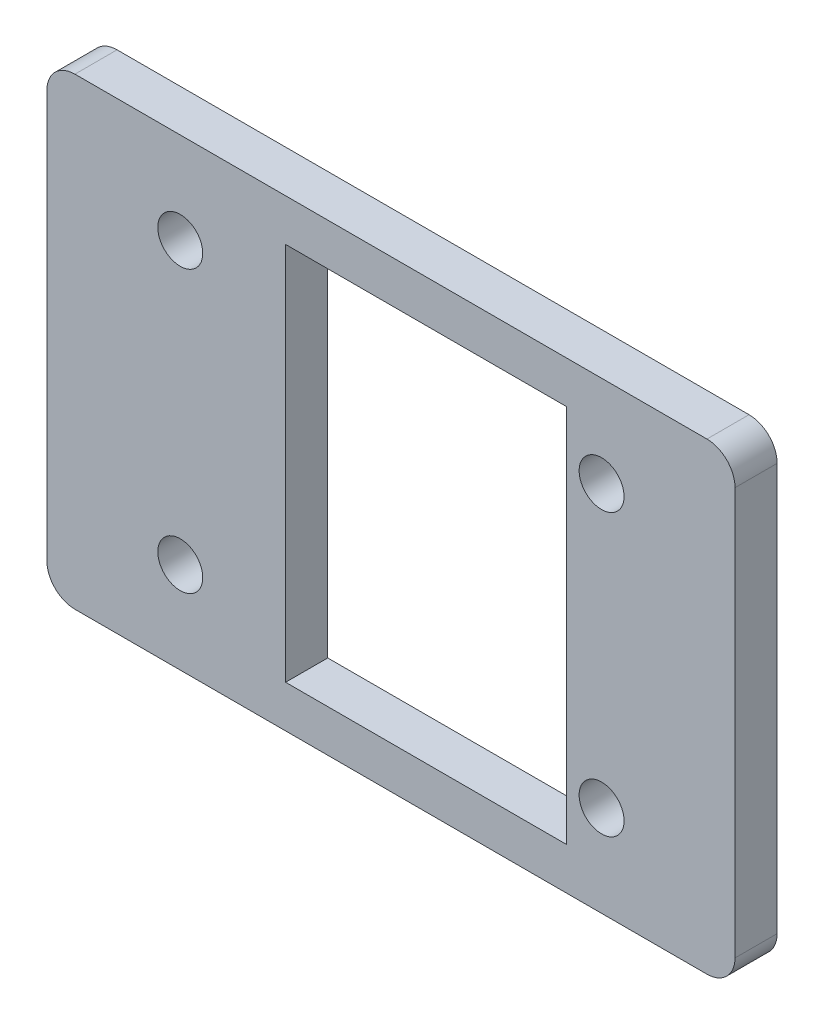
SolidWorks part; units mm, degrees
ref_plane "Front" through (0, 0, 0) normal (0, 0, 1) x (1, 0, 0)
ref_plane "Top" through (0, 0, 0) normal (0, 1, 0) x (1, 0, 0)
ref_plane "Right" through (0, 0, 0) normal (1, 0, 0) x (0, 0, -1)
sketch "Sketch1" plane through (0, 0, 0) normal (0, 0, 1) x (1, 0, 0)
  line L1 (-19.1679, 16.2582) -> (29.8321, 16.2582)
  line L2 (-19.1679, 16.2582) -> (-19.1679, -16.7418)
  line L3 (-19.1679, -16.7418) -> (29.8321, -16.7418)
  line L4 (29.8321, 16.2582) -> (29.8321, -16.7418)
  circle A0 centre (-9.6679, 9.7582) radius 1.6
  circle A1 centre (20.3321, 9.7582) radius 1.6
  circle A2 centre (-9.6679, -10.2418) radius 1.6
  circle A3 centre (20.3321, -10.2418) radius 1.6
  dimension "D7" = 3.2
  dimension "D8" = 3.2
  dimension "D9" = 3.2
  dimension "D10" = 3.2
  dimension "D1" = 49
  dimension "D2" = 33
extrude "Boss-Extrude2" add sketch "Sketch1" along normal blind 3
fillet "Fillet1" radius 2 4 edges at (-19.1679, -16.7418, 1.5) (29.8321, -16.7418, 1.5) (29.8321, 16.2582, 1.5) (-19.1679, 16.2582, 1.5)
sketch "Sketch2" plane through (0, 0, 3) normal (0, 0, 1) x (1, 0, 0)
  line L0 (-17.1679, -16.7418) -> (27.8321, -16.7418) construction
  line L1 (17.8321, 13.2582) -> (-2.1679, 13.2582)
  line L2 (17.8321, 13.2582) -> (17.8321, -13.7418)
  line L3 (17.8321, -13.7418) -> (-2.1679, -13.7418)
  line L4 (-2.1679, 13.2582) -> (-2.1679, -13.7418)
  line L5 (27.8321, 16.2582) -> (-17.1679, 16.2582) construction
  line L6 (29.8321, -14.7418) -> (29.8321, 14.2582) construction
  dimension "D1" = 20
  dimension "D2" = 3
  dimension "D3" = 3
  dimension "D4" = 12
extrude "Cut-Extrude1" cut sketch "Sketch2" against normal blind 10 contours L2 L1 L4 L3
